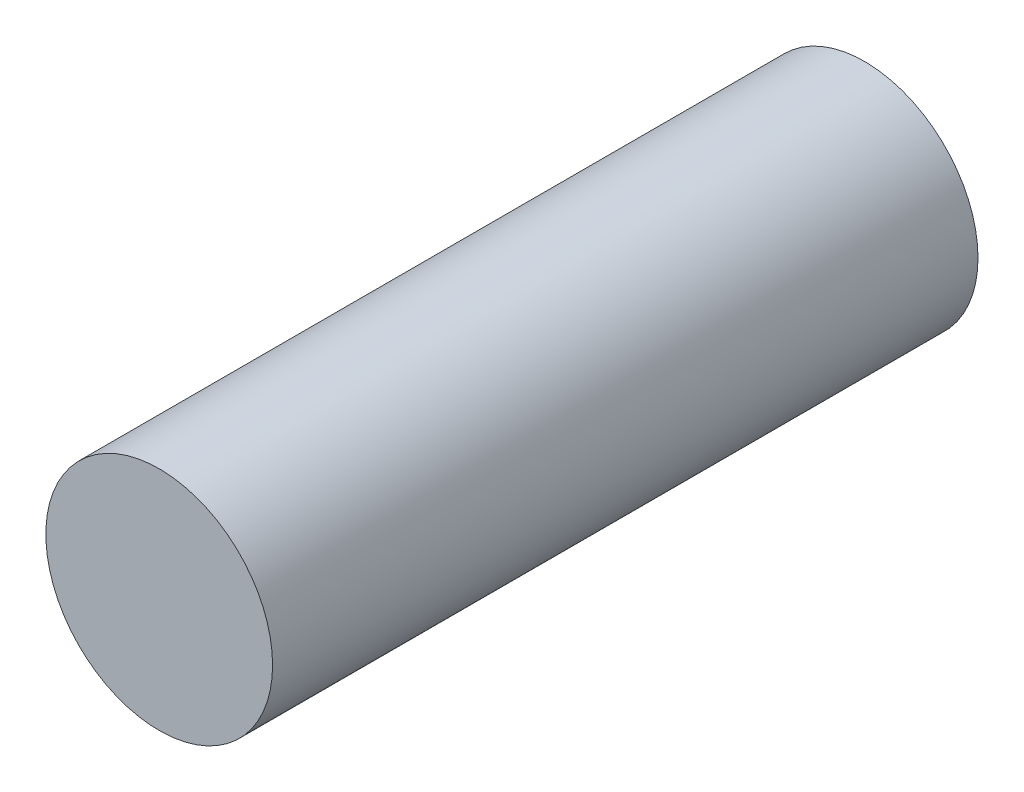
SolidWorks part; units mm, degrees
ref_plane "Front Plane" through (0, 0, 0) normal (0, 0, 1) x (1, 0, 0)
ref_plane "Top Plane" through (0, 0, 0) normal (0, 1, 0) x (1, 0, 0)
ref_plane "Right Plane" through (0, 0, 0) normal (1, 0, 0) x (0, 0, -1)
sketch "Sketch1" plane through (0, 0, 0) normal (0, 0, 1) x (1, 0, 0)
  circle A0 centre (0, 0) radius 4.5
  dimension "D1" = 9
extrude "Boss-Extrude1" add sketch "Sketch1" along normal blind 28
